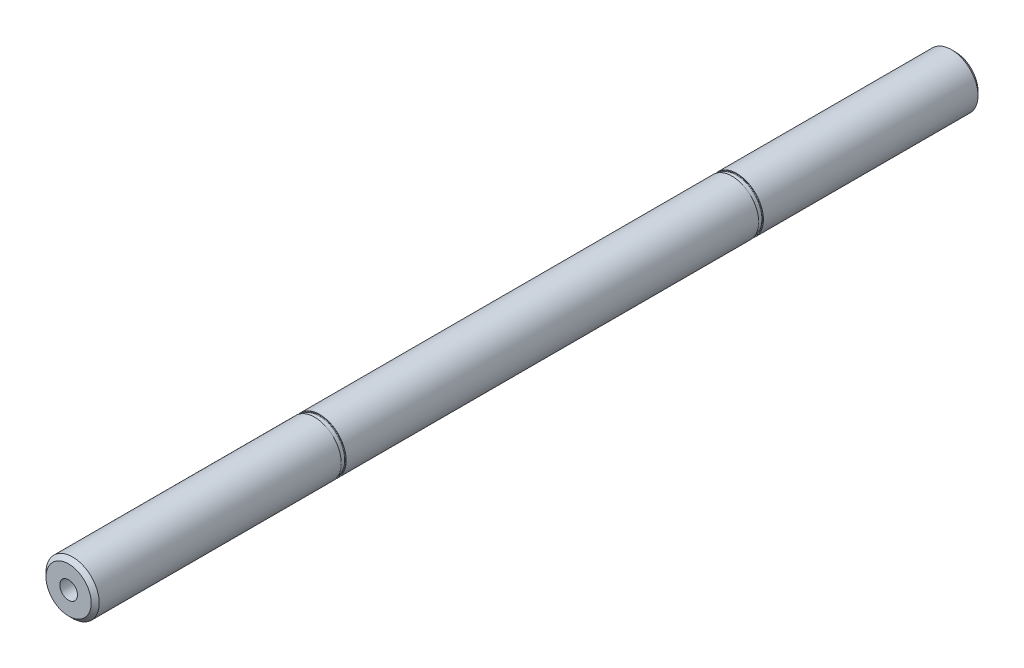
SolidWorks part; units mm, degrees
ref_plane "Front" through (0, 0, 0) normal (0, 0, 1) x (1, 0, 0)
ref_plane "Top" through (0, 0, 0) normal (0, 1, 0) x (1, 0, 0)
ref_plane "Right" through (0, 0, 0) normal (1, 0, 0) x (0, 0, -1)
sketch "Sketch1" plane through (0, 0, 0) normal (0, 0, 1) x (1, 0, 0)
  circle A0 centre (0, 0) radius 6
  dimension "OD" = 12
extrude "Extrude1" add sketch "Sketch1" along normal mid plane 200
chamfer "Chamfer1" distance 0.9 angle 45 2 edges at (6, 0, -100) (6, 0, 100)
sketch "Sketch2" plane through (0, 0, 0) normal (0, 0, 1) x (1, 0, 0)
  circle A0 centre (0, 0) radius 2
  dimension "ID" = 4
extrude "Extrude3" cut sketch "Sketch2" against normal through all and the other way through all
ref_plane "Plane1" through (0, 6, 0) normal (0, 1, 0) x (1, 0, 0)
ref_plane "Plane2" through (0, 0, 100) normal (-1, 0, 0) x (0, 1, 0)
sketch "Sketch5" plane through (0, 0, 100) normal (-1, 0, 0) x (0, 1, 0)
  line L0 (5.86, 55.5) -> (7.2, 55.5)
  line L1 (7.2, 55.5) -> (7.2, 56.6)
  line L2 (7.2, 56.6) -> (5.86, 56.6)
  line L3 (5.75, 56.49) -> (5.75, 55.61)
  line L4 (0, -50) -> (0, 50) construction
  arc A0 (5.75, 55.61) -> (5.86, 55.5) centre (5.86, 55.61) ccw
  arc A1 (5.75, 56.49) -> (5.86, 56.6) centre (5.86, 56.49) cw
  dimension "D1" = 0.11
  dimension "D2" = 0.11
  dimension "D3" = 55.5
revolve "Groove for DIN 471 - 12 x 1, Circlip for shafts - normal1" cut sketch "Sketch5"
ref_plane "Plane3" through (0, 0, 100) normal (-1, 0, 0) x (0, 1, 0)
sketch "Sketch7" plane through (0, 0, 100) normal (-1, 0, 0) x (0, 1, 0)
  line L0 (5.899, 149.6072) -> (7.1982, 150.1)
  line L1 (7.1982, 150.1) -> (7.2, 150.7)
  line L2 (7.2, 150.7) -> (5.86, 150.7)
  line L3 (5.75, 150.59) -> (5.75, 149.71)
  line L4 (0, -50) -> (0, 50) construction
  line L6 (-6, 56.6) -> (6, 56.6) construction
  arc A0 (5.75, 149.71) -> (5.899, 149.6072) centre (5.86, 149.71) ccw
  arc A1 (5.75, 150.59) -> (5.86, 150.7) centre (5.86, 150.59) cw
  dimension "D1" = 0.11
  dimension "D2" = 0.11
  dimension "D3" = 93.5
revolve "Groove for DIN 471 - 12 x 1, Circlip for shafts - normal2" cut sketch "Sketch7" angle 360 about L4
equation "\"D1@Chamfer1\" = \"OD@Sketch1\" * .075"
